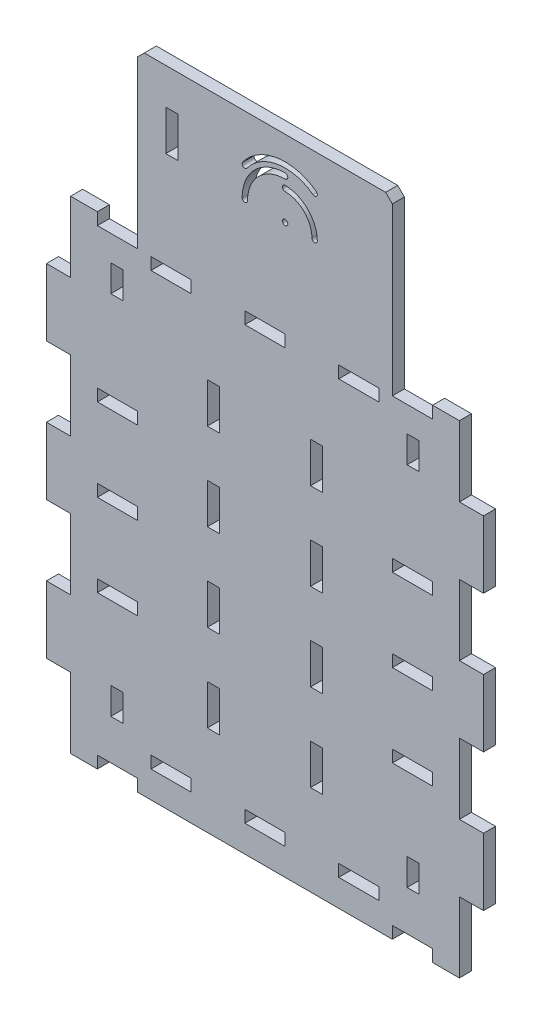
SolidWorks part; units mm, degrees
ref_plane "Front Plane" through (0, 0, 0) normal (0, 0, 1) x (1, 0, 0)
ref_plane "Top Plane" through (0, 0, 0) normal (0, 1, 0) x (1, 0, 0)
ref_plane "Right Plane" through (0, 0, 0) normal (1, 0, 0) x (0, 0, -1)
sketch "Model" plane through (0, 0, 0) normal (0, 0, 1) x (1, 0, 0)
  line L0 (-95, 175.5) -> (-95, 122.9) construction
  line L1 (-34, 132.5) -> (-34, 97.5) construction
  line L2 (-90, 480) -> (-95, 475)
  line L3 (-95, 237.1) -> (-95, 184.5) construction
  line L4 (-34, 197.5) -> (-34, 162.5) construction
  line L5 (-34, 262.5) -> (-34, 227.5) construction
  line L6 (90, 480) -> (95, 475)
  line L7 (-95, 445) -> (95, 445) construction
  line L8 (-95, 423) -> (95, 423) construction
  line L9 (37.03, 423) -> (37.03, 453.06) construction
  line L10 (-73.97, 453.03) -> (-64.97, 453.03)
  line L11 (-73.97, 453.03) -> (-73.97, 423.03)
  line L12 (-73.97, 423.03) -> (-64.97, 423.03)
  line L13 (-64.97, 453.03) -> (-64.97, 423.03)
  line L14 (-73.97, 453.03) -> (-64.97, 423.03) construction
  line L15 (-73.97, 423.03) -> (-64.97, 453.03) construction
  line L16 (37.03, 438.03) -> (-95, 438.03) construction
  line L167 (125, 360) -> (145, 360)
  line L168 (95, 0) -> (95, 9)
  line L169 (-145, 0) -> (-145, 52.5)
  line L170 (-145, 360) -> (-125, 360)
  line L171 (145, 0) -> (145, 52.5)
  line L172 (0, 0) -> (0, 480) construction
  line L174 (-90, 480) -> (90, 480)
  line L176 (125, 360) -> (125, 351)
  line L177 (95, 351) -> (125, 351)
  line L178 (-95, 475) -> (-95, 351)
  line L179 (-95, 351) -> (-125, 351)
  line L180 (-125, 360) -> (-125, 351)
  line L181 (95, 475) -> (95, 351)
  line L182 (-95, 0) -> (95, 0)
  line L183 (95, 9) -> (125, 9)
  line L184 (-95, 0) -> (-95, 9)
  line L185 (-95, 9) -> (-125, 9)
  line L186 (-125, 0) -> (-125, 9)
  line L187 (125, 0) -> (125, 9)
  line L188 (-125, 9) -> (-125, 0)
  line L189 (-125, 0) -> (-145, 0)
  line L190 (163, 180) -> (-163, 180) construction
  line L191 (125, 0) -> (145, 0)
  line L192 (-125, 184.5) -> (-95, 184.5)
  line L193 (-125, 184.5) -> (-125, 175.5)
  line L194 (-125, 175.5) -> (-95, 175.5)
  line L195 (-95, 184.5) -> (-95, 175.5)
  line L196 (-145, 205) -> (-163, 205)
  line L197 (-145, 307.5) -> (-163, 307.5)
  line L198 (-145, 155) -> (-163, 155)
  line L199 (-163, 205) -> (-163, 155)
  line L200 (-145, 205) -> (-145, 257.5)
  line L201 (-163, 307.5) -> (-163, 257.5)
  line L202 (-145, 257.5) -> (-163, 257.5)
  line L203 (-145, 102.5) -> (-163, 102.5)
  line L204 (-163, 102.5) -> (-163, 52.5)
  line L205 (-145, 52.5) -> (-163, 52.5)
  line L206 (-145, 307.5) -> (-145, 360)
  line L207 (-145, 102.5) -> (-145, 155)
  line L208 (-125, 246.1) -> (-125, 237.1)
  line L209 (-125, 237.1) -> (-95, 237.1)
  line L210 (-95, 246.1) -> (-95, 237.1)
  line L211 (-125, 246.1) -> (-95, 246.1)
  line L212 (-125, 122.9) -> (-125, 113.9)
  line L213 (-125, 113.9) -> (-95, 113.9)
  line L214 (-95, 122.9) -> (-95, 113.9)
  line L215 (-125, 122.9) -> (-95, 122.9)
  line L216 (-34, 227.5) -> (-34, 197.5)
  line L217 (-43, 292.5) -> (-34, 292.5)
  line L218 (-43, 292.5) -> (-43, 262.5)
  line L219 (-43, 262.5) -> (-34, 262.5)
  line L220 (-34, 292.5) -> (-34, 262.5)
  line L221 (-43, 197.5) -> (-34, 197.5)
  line L222 (-43, 227.5) -> (-43, 197.5)
  line L223 (-43, 227.5) -> (-34, 227.5)
  line L224 (-34, 162.5) -> (-34, 132.5)
  line L225 (-43, 132.5) -> (-34, 132.5)
  line L226 (-43, 162.5) -> (-43, 132.5)
  line L227 (-43, 162.5) -> (-34, 162.5)
  line L228 (-34, 97.5) -> (-34, 67.5)
  line L229 (-43, 67.5) -> (-34, 67.5)
  line L230 (-43, 97.5) -> (-43, 67.5)
  line L231 (-43, 97.5) -> (-34, 97.5)
  line L232 (-85, 342) -> (-55, 342)
  line L233 (-15, 29) -> (15, 29)
  line L234 (-15, 29) -> (-15, 20)
  line L235 (-15, 20) -> (15, 20)
  line L236 (15, 29) -> (15, 20)
  line L237 (-115, 332) -> (-106, 332)
  line L238 (-115, 332) -> (-115, 312)
  line L239 (-115, 312) -> (-106, 312)
  line L240 (-85, 29) -> (-55, 29)
  line L241 (-55, 29) -> (-55, 20)
  line L242 (-85, 20) -> (-55, 20)
  line L243 (-85, 29) -> (-85, 20)
  line L244 (-106, 332) -> (-106, 312)
  line L245 (-115, 59) -> (-106, 59)
  line L246 (-115, 59) -> (-115, 39)
  line L247 (-115, 39) -> (-106, 39)
  line L248 (-106, 59) -> (-106, 39)
  line L249 (-15, 351) -> (15, 351)
  line L250 (-15, 351) -> (-15, 342)
  line L251 (-15, 342) -> (15, 342)
  line L252 (15, 351) -> (15, 342)
  line L253 (-55, 351) -> (-55, 342)
  line L254 (-85, 351) -> (-55, 351)
  line L255 (-85, 351) -> (-85, 342)
  line L268 (85, 351) -> (85, 342)
  line L269 (85, 351) -> (55, 351)
  line L270 (55, 351) -> (55, 342)
  line L271 (85, 342) -> (55, 342)
  line L284 (145, 52.5) -> (163, 52.5)
  line L285 (163, 102.5) -> (163, 52.5)
  line L286 (145, 102.5) -> (163, 102.5)
  line L287 (145, 155) -> (163, 155)
  line L288 (163, 205) -> (163, 155)
  line L289 (145, 205) -> (163, 205)
  line L290 (145, 257.5) -> (163, 257.5)
  line L291 (145, 307.5) -> (163, 307.5)
  line L292 (163, 307.5) -> (163, 257.5)
  line L293 (145, 307.5) -> (145, 360)
  line L294 (145, 102.5) -> (145, 155)
  line L295 (145, 205) -> (145, 257.5)
  line L296 (125, 122.9) -> (125, 113.9)
  line L297 (95, 122.9) -> (95, 113.9)
  line L298 (125, 122.9) -> (95, 122.9)
  line L299 (125, 113.9) -> (95, 113.9)
  line L300 (125, 184.5) -> (125, 175.5)
  line L301 (95, 184.5) -> (95, 175.5)
  line L302 (125, 175.5) -> (95, 175.5)
  line L303 (125, 184.5) -> (95, 184.5)
  line L304 (125, 246.1) -> (125, 237.1)
  line L305 (95, 246.1) -> (95, 237.1)
  line L306 (125, 246.1) -> (95, 246.1)
  line L307 (125, 237.1) -> (95, 237.1)
  line L308 (115, 332) -> (106, 332)
  line L309 (106, 332) -> (106, 312)
  line L310 (115, 332) -> (115, 312)
  line L311 (115, 312) -> (106, 312)
  line L312 (34, 292.5) -> (34, 262.5)
  line L313 (43, 292.5) -> (34, 292.5)
  line L314 (43, 292.5) -> (43, 262.5)
  line L315 (43, 262.5) -> (34, 262.5)
  line L316 (43, 227.5) -> (34, 227.5)
  line L317 (43, 227.5) -> (43, 197.5)
  line L318 (34, 227.5) -> (34, 197.5)
  line L319 (43, 197.5) -> (34, 197.5)
  line L320 (43, 162.5) -> (34, 162.5)
  line L321 (43, 162.5) -> (43, 132.5)
  line L322 (34, 162.5) -> (34, 132.5)
  line L323 (43, 132.5) -> (34, 132.5)
  line L324 (43, 97.5) -> (43, 67.5)
  line L325 (43, 97.5) -> (34, 97.5)
  line L326 (34, 97.5) -> (34, 67.5)
  line L327 (43, 67.5) -> (34, 67.5)
  line L328 (115, 59) -> (106, 59)
  line L329 (115, 59) -> (115, 39)
  line L330 (106, 59) -> (106, 39)
  line L331 (115, 39) -> (106, 39)
  line L332 (85, 29) -> (85, 20)
  line L333 (85, 20) -> (55, 20)
  line L334 (85, 29) -> (55, 29)
  line L335 (55, 29) -> (55, 20)
  arc A0 (37.03, 423) -> (15.03, 445) centre (15.03, 423) ccw construction
  circle A1 centre (15.03, 423) radius 2
  arc A2 (39.03, 423) -> (15.03, 447) centre (15.03, 423) ccw
  arc A3 (35.03, 423) -> (15.03, 443) centre (15.03, 423) ccw
  arc A4 (35.03, 423) -> (39.03, 423) centre (37.03, 423) ccw
  arc A5 (15.03, 447) -> (15.03, 443) centre (15.03, 445) ccw
  arc A6 (37.03, 453.06) -> (-15.03, 445) centre (15.03, 423) ccw construction
  arc A7 (38.2112, 454.6739) -> (-16.6439, 446.1812) centre (15.03, 423) ccw
  arc A8 (35.8488, 451.4461) -> (-13.4161, 443.8188) centre (15.03, 423) ccw
  arc A9 (35.8488, 451.4461) -> (38.2112, 454.6739) centre (37.03, 453.06) ccw
  arc A10 (-16.6439, 446.1812) -> (-13.4161, 443.8188) centre (-15.03, 445) ccw
  arc A11 (15.03, 453.06) -> (-15.03, 423) centre (15.03, 423) ccw construction
  arc A12 (15.03, 455.06) -> (-17.03, 423) centre (15.03, 423) ccw
  arc A13 (15.03, 451.06) -> (-13.03, 423) centre (15.03, 423) ccw
  arc A14 (15.03, 451.06) -> (15.03, 455.06) centre (15.03, 453.06) ccw
  arc A15 (-17.03, 423) -> (-13.03, 423) centre (-15.03, 423) ccw
  point P0 (-34, 180)
  point P1 (-15.03, 445)
  point P2 (15.03, 445)
  point P7 (-15.03, 423)
  point P8 (15.03, 423)
  point P9 (37.03, 423)
  point P12 (30.5863, 438.5563)
  point P19 (37.03, 453.06)
  point P20 (15.03, 453.06)
  point P24 (9.3307, 459.812)
  point P32 (-6.2256, 444.2556)
  point P37 (-69.47, 438.03)
  point P201 (0, 480)
  point P225 (-125, 180)
  point P226 (-163, 180)
  point P263 (0, 29)
  point P280 (0, 351)
  dimension "D33" = 4
  dimension "D17" = 9
  dimension "D18" = 9
  dimension "D26" = 9
  dimension "D32" = 18
  dimension "D39" = 9
  dimension "D41" = 30
  dimension "D51" = 9
  dimension "D54" = 9
  dimension "D56" = 20
  dimension "D36" = 40
  dimension "D9" = 360
  dimension "D10" = 30
  dimension "D11" = 20
  dimension "D12" = 40
  dimension "D15" = 30
  dimension "D7" = 120
  dimension "D16" = 95
  dimension "D19" = 50
  dimension "D20" = 290
  dimension "D21" = 34
  dimension "D22" = 35
  dimension "D23" = 10
  dimension "D24" = 10
  dimension "D14" = 115
  dimension "D49" = 52.6
  dimension "D50" = 5
  dimension "D52" = 135
  dimension "D8" = 35
  dimension "D25" = 22
  dimension "D13" = 22
  dimension "D27" = 4
  dimension "D6" = 30.06
  dimension "D29" = 30.06
  dimension "D35" = 4
  dimension "D38" = 4
  dimension "D40" = 9
  dimension "D42" = 30
  dimension "D43" = 80
  dimension "D30" = 2
  dimension "D31" = 2
  dimension "D28" = 2
  dimension "D37" = 2
  dimension "D47" = 4
  dimension "D57" = 2
  dimension "D34" = 2
extrude "Boss-Extrude1" add sketch "Model" along normal blind 9
equation "\"material-thickness\" = 9mm"
equation "\"baseplate-width\" = 290mm"
equation "\"baseplate-height\" = 360mm"
equation "\"tab-width-small\" = 20mm ' Width of the small version of the Tab"
equation "\"tab-width-large\" = 30mm ' Width of the large version of the Tab"
equation "\"plate-supporttab-gapwidth\" = 40mm"
equation "\"plate-supporttab-gapheight\" = 20mm"
equation "\"motor-slot-width\"= 4mm"
equation "\"D17@Model\" = \"material-thickness\""
equation "\"D18@Model\" = \"material-thickness\""
equation "\"D26@Model\" = \"material-thickness\""
equation "\"D32@Model\"=\"material-thickness\"*2"
equation "\"D39@Model\" = \"material-thickness\""
equation "\"D51@Model\" = \"material-thickness\""
equation "\"D54@Model\" = \"material-thickness\""
equation "\"D1@Boss-Extrude1\" = \"material-thickness\""
equation "\"D10@Model\"=\"tab-width-large\""
equation "\"D15@Model\"=\"tab-width-large\""
equation "\"D41@Model\"=\"tab-width-large\""
equation "\"D56@Model\"=\"tab-width-small\""
equation "\"D20@Model\"=\"baseplate-width\""
equation "\"D9@Model\"=\"baseplate-height\""
equation "\"D33@Model\"=\"motor-slot-width\""
equation "\"D27@Model\"=\"motor-slot-width\""
equation "\"D35@Model\"=\"motor-slot-width\""
equation "\"D38@Model\"=\"motor-slot-width\""
equation "\"D40@Model\"=\"material-thickness\""
equation "\"D42@Model\"=\"tab-width-large\""
